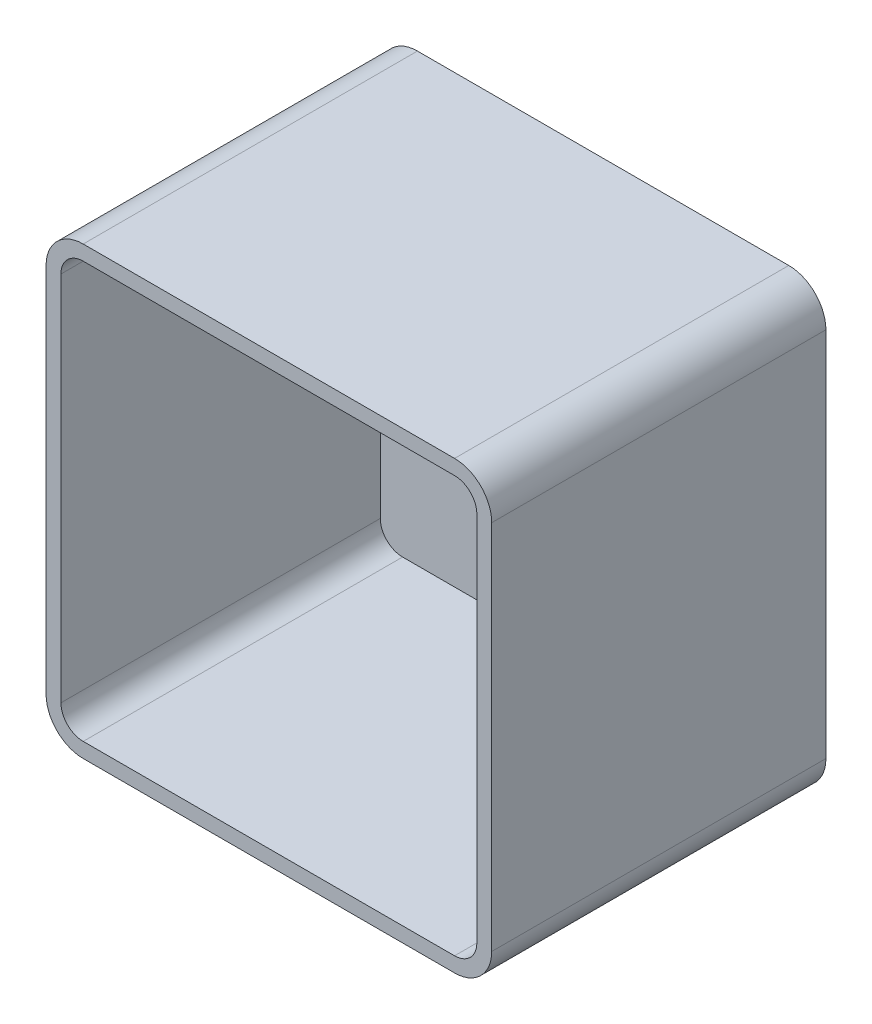
SolidWorks part; units mm, degrees
ref_plane "Front Plane" through (0, 0, 0) normal (0, 0, 1) x (1, 0, 0)
ref_plane "Top Plane" through (0, 0, 0) normal (0, 1, 0) x (1, 0, 0)
ref_plane "Right Plane" through (0, 0, 0) normal (1, 0, 0) x (0, 0, -1)
sketch "Sketch1" plane through (0, 0, 0) normal (0, 0, 1) x (1, 0, 0)
  line L1 (0, 0) -> (120, 0)
  line L2 (0, 0) -> (0, 120)
  line L3 (0, 120) -> (120, 120)
  line L4 (120, 0) -> (120, 120)
  dimension "D1" = 120
extrude "Boss-Extrude1" add sketch "Sketch1" along normal blind 90
fillet "Fillet1" radius 10 4 edges at (0, 0, 45) (0, 120, 45) (120, 0, 45) (120, 120, 45)
shell "Shell1" thickness 4
